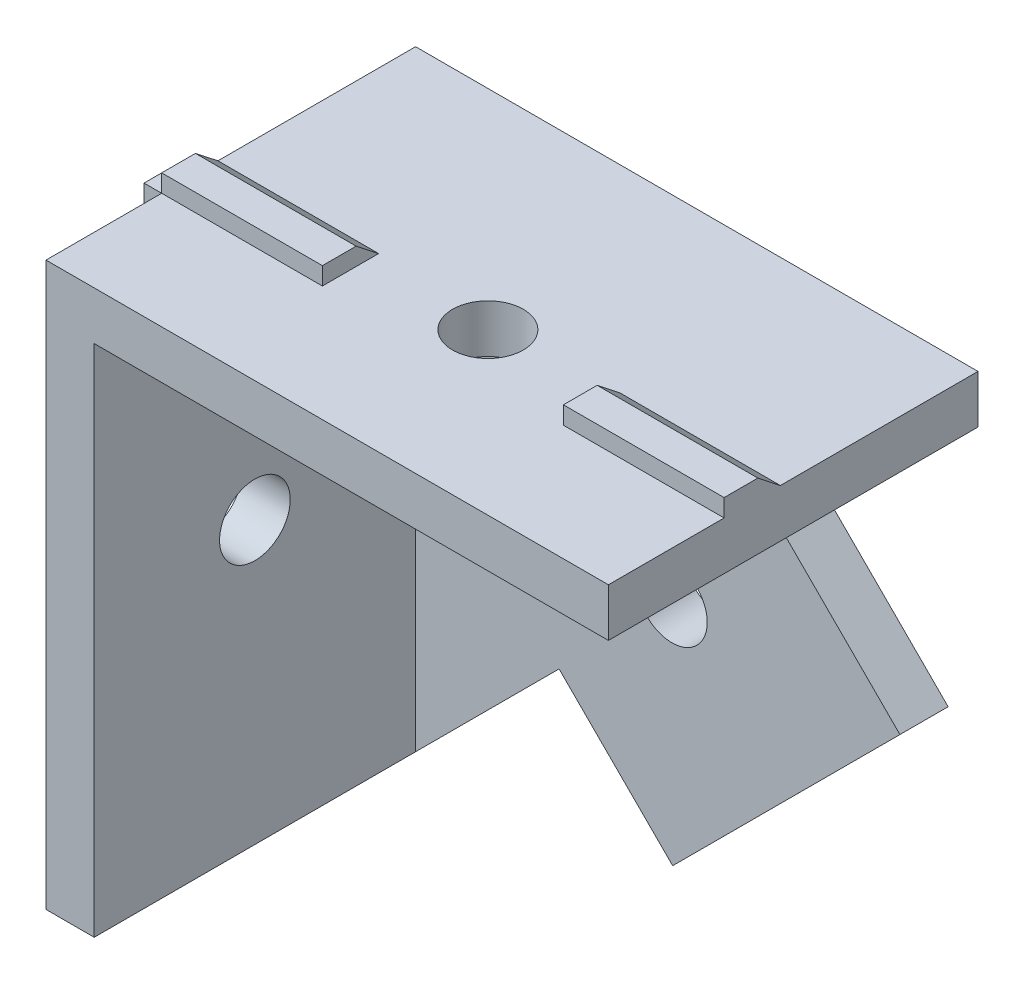
SolidWorks part; units mm, degrees
material "ABS"
ref_plane "Front Plane" through (0, 0, 0) normal (0, 0, 1) x (1, 0, 0)
ref_plane "Top Plane" through (0, 0, 0) normal (0, 1, 0) x (1, 0, 0)
ref_plane "Right Plane" through (0, 0, 0) normal (1, 0, 0) x (0, 0, -1)
sketch "Sketch1" plane through (0, 0, 0) normal (0, 0, 1) x (1, 0, 0)
  line L0 (0, -35) -> (0, 0)
  line L1 (0, 0) -> (35, 0)
  line L2 (35, 0) -> (35, -3)
  line L3 (35, -3) -> (3, -35)
  line L4 (3, -35) -> (0, -35)
  dimension "D1" = 35
  dimension "D2" = 35
  dimension "D3" = 3
  dimension "D4" = 3
extrude "Boss-Extrude1" add sketch "Sketch1" along normal blind 3
sketch "Sketch2" plane through (0, 0, 3) normal (0, 0, 1) x (1, 0, 0)
  line L0 (0, -35) -> (0, 0)
  line L1 (0, 0) -> (35, 0)
  line L2 (35, 0) -> (35, -3)
  line L3 (35, -3) -> (3, -3)
  line L4 (3, -3) -> (3, -35)
  line L5 (3, -35) -> (0, -35)
extrude "Boss-Extrude2" add sketch "Sketch2" along normal blind 20
sketch "Sketch4" plane through (0, -3, 0) normal (0, -1, 0) x (1, 0, 0)
  line L0 (35, 23) -> (35, 3) construction
  line L1 (3, 0) -> (35, 0) construction
  circle A0 centre (17.5, 13) radius 2.2
  dimension "D1" = 4.4
  dimension "D2" = 17.5
  dimension "D3" = 13
extrude "Cut-Extrude1" cut sketch "Sketch4" against normal through all
sketch "Sketch5" plane through (3, 0, 0) normal (1, 0, 0) x (0, 0, -1)
  line L0 (0, -35) -> (0, -3) construction
  line L1 (-23, -35) -> (-3, -35) construction
  circle A0 centre (-13, -17.5) radius 2.2
  dimension "D1" = 13
  dimension "D2" = 4.4
  dimension "D3" = 17.5
extrude "Cut-Extrude2" cut sketch "Sketch5" against normal through all
sketch "Sketch6" plane through (35, 0, 0) normal (1, 0, 0) x (0, 0, -1)
  line L0 (-15.8, 0) -> (-15.8, 1.1)
  line L1 (-23, 0) -> (0, 0) construction
  line L2 (-15.8, 1.1) -> (-13.7, 1.1)
  line L3 (-13.7, 1.1) -> (-12.3, 0)
  line L4 (-12.3, 0) -> (-15.8, 0)
  line L5 (-23, -3) -> (-23, 0) construction
  dimension "D1" = 1.1
  dimension "D2" = 2.1
  dimension "D3" = 7.2
  dimension "D4" = 3.5
extrude "Boss-Extrude5" add sketch "Sketch6" against normal through all
sketch "Sketch7" plane through (0, 0, 15.8) normal (0, 0, 1) x (1, 0, 0)
  line L0 (0, 1.1) -> (35, 1.1) construction
  line L1 (25, 1.1) -> (10, 1.1)
  line L2 (25, 1.1) -> (25, 0)
  line L3 (25, 0) -> (10, 0)
  line L4 (10, 1.1) -> (10, 0)
  line L5 (0, 0) -> (35, 0) construction
  line L6 (35, 1.1) -> (35, 0) construction
  dimension "D1" = 10
  dimension "D2" = 15
extrude "Cut-Extrude3" cut sketch "Sketch7" against normal through all
sketch "Sketch8" plane through (0, -35, 0) normal (0, -1, 0) x (1, 0, 0)
  line L0 (0, 12.3) -> (0, 15.8)
  line L1 (0, 23) -> (0, 0) construction
  line L2 (0, 15.8) -> (-1.1, 15.8)
  line L3 (-1.1, 15.8) -> (-1.1, 13.7)
  line L4 (-1.1, 13.7) -> (0, 12.3)
  line L5 (0, 23) -> (3, 23) construction
  dimension "D1" = 1.1
  dimension "D2" = 2.1
  dimension "D3" = 7.2
  dimension "D4" = 3.5
extrude "Boss-Extrude6" add sketch "Sketch8" against normal up to surface (35 mm away) up to face at (15.8333, 0, 14.825)
sketch "Sketch9" plane through (0, 0, 15.8) normal (0, 0, 1) x (1, 0, 0)
  line L0 (0, 0) -> (0, -35) construction
  line L1 (0, -10) -> (-1.1, -10)
  line L2 (0, -10) -> (0, -25)
  line L3 (0, -25) -> (-1.1, -25)
  line L4 (-1.1, -10) -> (-1.1, -25)
  line L5 (-1.1, 0) -> (-1.1, -35) construction
  line L6 (0, -35) -> (-1.1, -35) construction
  dimension "D1" = 15
  dimension "D2" = 10
extrude "Cut-Extrude4" cut sketch "Sketch9" against normal through all
sketch "Sketch10" plane through (0, 0, 3) normal (0, 0, 1) x (1, 0, 0)
  line L0 (11.9286, -26.0714) -> (26.0706, -11.9294)
  line L1 (3, -35) -> (35, -3) construction
  line L2 (26.0706, -11.9294) -> (33.142, -19.002)
  line L3 (33.142, -19.002) -> (18.9989, -33.1429)
  line L4 (18.9989, -33.1429) -> (11.9286, -26.0714)
  line L5 (3, -3.002) -> (26.072, -11.93) construction
extrude "Boss-Extrude7" add sketch "Sketch10" against normal up to surface (3 mm away) up to face at (14.6, -14.6, 0)
sketch "Sketch11" plane through (0, 0, 3) normal (0, 0, 1) x (1, 0, 0)
  circle A0 centre (18.951, -18.952) radius 2.2
extrude "Cut-Extrude5" cut sketch "Sketch11" against normal through all
